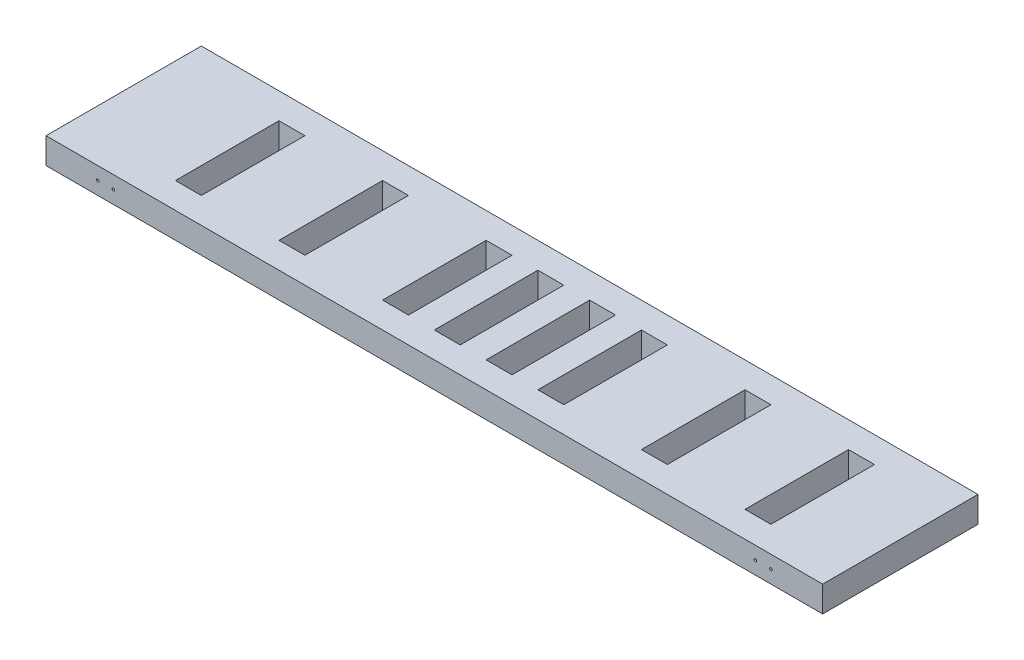
SolidWorks part; units mm, degrees
ref_plane "Front Plane" through (0, 0, 0) normal (0, 0, 1) x (1, 0, 0)
ref_plane "Top Plane" through (0, 0, 0) normal (0, 1, 0) x (1, 0, 0)
ref_plane "Right Plane" through (0, 0, 0) normal (1, 0, 0) x (0, 0, -1)
sketch "Sketch1" plane through (0, 0, 0) normal (0, 1, 0) x (1, 0, 0)
  line L1 (-750, 150) -> (750, 150)
  line L2 (-750, 150) -> (-750, -150)
  line L3 (-750, -150) -> (750, -150)
  line L4 (750, 150) -> (750, -150)
  line L5 (-750, 150) -> (750, -150) construction
  line L6 (-750, -150) -> (750, 150) construction
  point P0 (0, 0)
  dimension "D1" = 1500
  dimension "D2" = 300
extrude "Boss-Extrude1" add sketch "Sketch1" along normal blind 50
sketch "Sketch2" plane through (0, 0, 150) normal (0, 0, 1) x (1, 0, 0)
  line L0 (-750, 0) -> (750, 0) construction
  line L1 (-750, 50) -> (-750, 0) construction
  line L2 (750, 50) -> (750, 0) construction
  circle A0 centre (-650, 25) radius 2.5
  circle A1 centre (-620, 25) radius 2.5
  circle A2 centre (620, 25) radius 2.5
  circle A3 centre (650, 25) radius 2.5
  dimension "D1" = 25
  dimension "D2" = 25
  dimension "D5" = 5
  dimension "D6" = 5
  dimension "D7" = 25
  dimension "D8" = 25
  dimension "D9" = 100
  dimension "D10" = 130
  dimension "D11" = 5
  dimension "D12" = 5
  dimension "D3" = 100
  dimension "D4" = 130
extrude "Cut-Extrude1" cut sketch "Sketch2" against normal blind 50
sketch "Sketch3" plane through (0, 50, 0) normal (0, 1, 0) x (1, 0, 0)
  line L0 (-750, 150) -> (-750, -150) construction
  line L1 (-550, 100) -> (-500, 100)
  line L2 (-550, 100) -> (-550, -100)
  line L3 (-550, -100) -> (-500, -100)
  line L4 (-500, 100) -> (-500, -100)
  line L5 (-350, 100) -> (-300, 100)
  line L6 (-350, 100) -> (-350, -100)
  line L7 (-350, -100) -> (-300, -100)
  line L8 (-300, 100) -> (-300, -100)
  line L9 (-150, 100) -> (-100, 100)
  line L10 (-150, 100) -> (-150, -100)
  line L11 (-150, -100) -> (-100, -100)
  line L12 (-100, 100) -> (-100, -100)
  line L13 (-50, 100) -> (0, 100)
  line L14 (-50, 100) -> (-50, -100)
  line L15 (-50, -100) -> (0, -100)
  line L16 (0, 100) -> (0, -100)
  line L17 (50, 100) -> (100, 100)
  line L18 (50, 100) -> (50, -100)
  line L19 (50, -100) -> (100, -100)
  line L20 (100, 100) -> (100, -100)
  line L21 (150, 100) -> (200, 100)
  line L22 (150, 100) -> (150, -100)
  line L23 (150, -100) -> (200, -100)
  line L24 (200, 100) -> (200, -100)
  line L25 (350, 100) -> (400, 100)
  line L26 (350, 100) -> (350, -100)
  line L27 (350, -100) -> (400, -100)
  line L28 (400, 100) -> (400, -100)
  line L29 (550, 100) -> (600, 100)
  line L30 (550, 100) -> (550, -100)
  line L31 (550, -100) -> (600, -100)
  line L32 (600, 100) -> (600, -100)
  line L33 (750, 150) -> (-750, 150) construction
  line L34 (750, -150) -> (750, 150) construction
  point P32 (-325, 100)
  point P35 (-525, 100)
  point P40 (50, 0)
  point P41 (175, 100)
  dimension "D1" = 50
  dimension "D2" = 200
  dimension "D3" = 200
  dimension "D4" = 50
  dimension "D5" = 150
  dimension "D6" = 150
  dimension "D7" = 150
  dimension "D8" = 150
  dimension "D9" = 50
  dimension "D10" = 50
  dimension "D11" = 50
  dimension "D12" = 50
  dimension "D13" = 50
  dimension "D14" = 50
  dimension "D15" = 50
  dimension "D16" = 50
extrude "Cut-Extrude2" cut sketch "Sketch3" against normal through all
